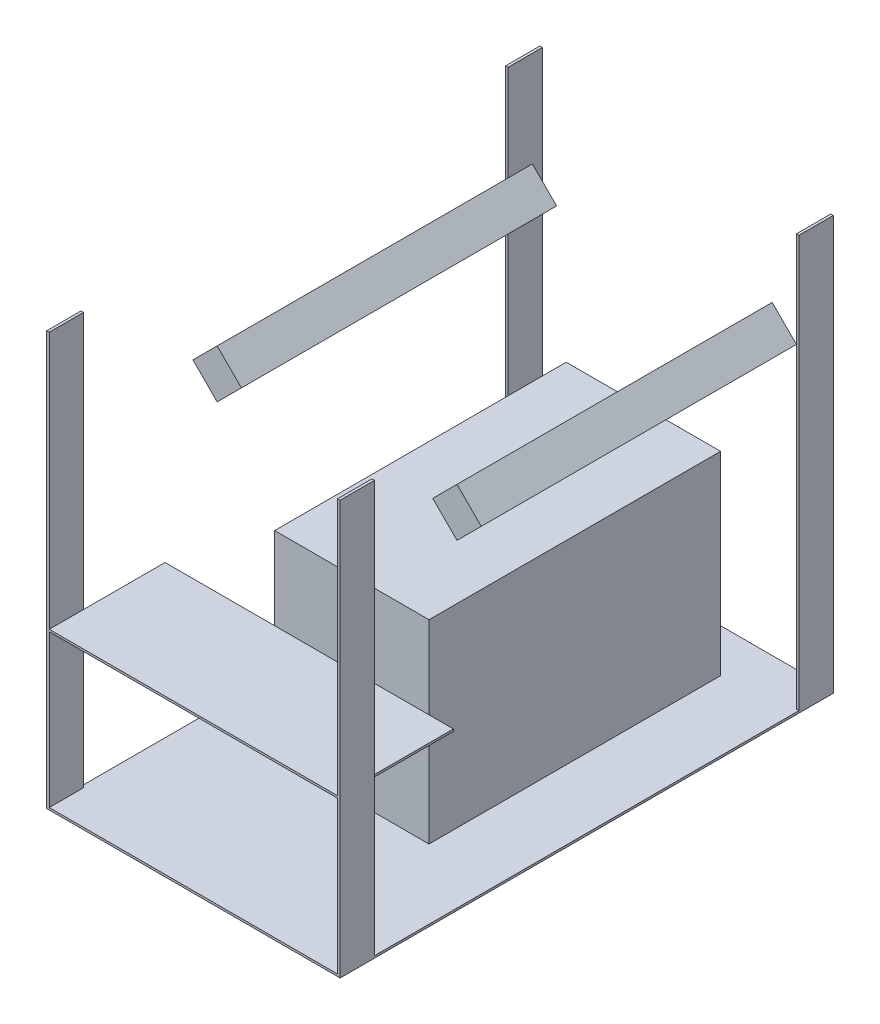
SolidWorks part; units mm, degrees
ref_plane "Front Plane" through (0, 0, 0) normal (0, 0, 1) x (1, 0, 0)
ref_plane "Top Plane" through (0, 0, 0) normal (0, 1, 0) x (1, 0, 0)
ref_plane "Right Plane" through (0, 0, 0) normal (1, 0, 0) x (0, 0, -1)
sketch "Sketch1" plane through (0, 0, 0) normal (0, 1, 0) x (1, 0, 0)
  line L1 (-217.297, 365.125) -> (217.297, 365.125)
  line L2 (-217.297, 365.125) -> (-217.297, -365.125)
  line L3 (-217.297, -365.125) -> (217.297, -365.125)
  line L4 (217.297, 365.125) -> (217.297, -365.125)
  line L5 (-217.297, 365.125) -> (217.297, -365.125) construction
  line L6 (-217.297, -365.125) -> (217.297, 365.125) construction
  line L8 (-217.297, -193.675) -> (217.297, -193.675) construction
  line L10 (-166.497, 310.007) -> (166.751, 310.007) construction
  line L11 (-166.497, 310.007) -> (-166.497, -139.573) construction
  line L12 (-166.497, -139.573) -> (166.751, -139.573) construction
  line L13 (166.751, 310.007) -> (166.751, -139.573) construction
  line L14 (-166.497, 310.007) -> (166.751, -139.573) construction
  line L15 (-166.497, -139.573) -> (166.751, 310.007) construction
  point P0 (0, 0)
  point P8 (0.127, 85.217)
  dimension "D1" = 434.594
  dimension "D2" = 730.25
  dimension "D3" = 171.45
  dimension "D4" = 333.248
  dimension "D5" = 449.58
  dimension "D6" = 55.118
  dimension "D7" = 50.8
extrude "Boss-Extrude1" add sketch "Sketch1" along normal blind 3.175
sketch "Sketch2" plane through (0, 3.175, 0) normal (0, 1, 0) x (1, 0, 0)
  line L0 (0, -1.7463) -> (0, 1.7463) construction
  line L1 (-217.297, -365.125) -> (-213.487, -365.125)
  line L2 (-217.297, -365.125) -> (-217.297, -314.325)
  line L3 (-217.297, -314.325) -> (-213.487, -314.325)
  line L4 (-213.487, -365.125) -> (-213.487, -314.325)
  line L18 (217.297, -314.325) -> (213.487, -314.325)
  line L19 (213.487, -365.125) -> (213.487, -314.325)
  line L20 (217.297, -365.125) -> (213.487, -365.125)
  line L21 (217.297, -365.125) -> (217.297, -314.325)
  line L22 (-1.7463, 0) -> (1.7463, 0) construction
  line L23 (217.297, 365.125) -> (217.297, 314.325)
  line L24 (217.297, 365.125) -> (213.487, 365.125)
  line L25 (213.487, 365.125) -> (213.487, 314.325)
  line L26 (217.297, 314.325) -> (213.487, 314.325)
  line L27 (-217.297, 314.325) -> (-213.487, 314.325)
  line L28 (-213.487, 365.125) -> (-213.487, 314.325)
  line L29 (-217.297, 365.125) -> (-213.487, 365.125)
  line L30 (-217.297, 365.125) -> (-217.297, 314.325)
  dimension "D1" = 3.81
  dimension "D2" = 50.8
extrude "Boss-Extrude2" add sketch "Sketch2" along normal blind 609.6
ref_plane "Plane1" through (0, 228.6, 0) normal (0, 1, 0) x (1, 0, 0)
sketch "Sketch3" plane through (0, 228.6, 0) normal (0, 1, 0) x (1, 0, 0)
  line L0 (213.487, -314.325) -> (213.487, -365.125) construction
  line L1 (-213.487, -365.125) -> (213.487, -365.125)
  line L2 (-213.487, -365.125) -> (-213.487, -193.675)
  line L3 (-213.487, -193.675) -> (213.487, -193.675)
  line L4 (213.487, -365.125) -> (213.487, -193.675)
  dimension "D1" = 171.45
extrude "Boss-Extrude3" add sketch "Sketch3" along normal blind 3.175
sketch "Sketch4" plane through (0, 3.175, 0) normal (0, 1, 0) x (1, 0, 0)
  line L1 (-114.173, 301.117) -> (114.427, 301.117)
  line L2 (-114.173, 301.117) -> (-114.173, -130.683)
  line L3 (-114.173, -130.683) -> (114.427, -130.683)
  line L4 (114.427, 301.117) -> (114.427, -130.683)
  line L5 (-114.173, 301.117) -> (114.427, -130.683) construction
  line L6 (-114.173, -130.683) -> (114.427, 301.117) construction
  point P0 (0.127, 85.217)
  dimension "D1" = 431.8
  dimension "D2" = 228.6
extrude "Boss-Extrude4" add sketch "Sketch4" along normal blind 287.655
ref_plane "Plane2" through (0, 0, 152.4) normal (0, 0, 1) x (1, 0, 0)
sketch "Sketch5" plane through (0, 0, 152.4) normal (0, 0, 1) x (1, 0, 0)
  line L0 (177.566, 506.817) -> (141.645, 470.896)
  line L1 (141.645, 470.896) -> (177.566, 434.975)
  line L2 (177.566, 434.975) -> (213.487, 470.896)
  line L3 (213.487, 470.896) -> (177.566, 506.817)
  line L4 (213.487, 612.775) -> (213.487, 231.775) construction
  line L5 (-213.487, 3.175) -> (213.487, 3.175) construction
  line L6 (0, -337.0263) -> (0, 337.0263) construction
  line L7 (-177.566, 434.975) -> (-213.487, 470.896)
  line L8 (-141.645, 470.896) -> (-177.566, 434.975)
  line L9 (-177.566, 506.817) -> (-141.645, 470.896)
  line L10 (-213.487, 470.896) -> (-177.566, 506.817)
  dimension "D1" = 50.8
  dimension "D2" = 50.8
  dimension "D3" = 45
  dimension "D4" = 431.8
extrude "Boss-Extrude5" add sketch "Sketch5" against normal up to surface (466.725 mm away) separate body up to face at (215.392, 307.975, -314.325)
sketch "Sketch6" plane through (0, 231.775, 0) normal (0, 1, 0) x (1, 0, 0)
  line L0 (-213.487, -279.4) -> (213.487, -279.4) construction
  line L1 (-213.487, -193.675) -> (-213.487, -314.325) construction
  line L2 (213.487, -314.325) -> (213.487, -193.675) construction
  line L3 (213.487, -193.675) -> (-213.487, -193.675) construction
  line L4 (0, -193.675) -> (0, -365.125) construction
  line L5 (-217.297, -193.675) -> (217.297, -193.675) construction
  line L6 (-217.297, -365.125) -> (217.297, -365.125) construction
  point P14 (0, -279.4)
  dimension "D1" = 85.725
